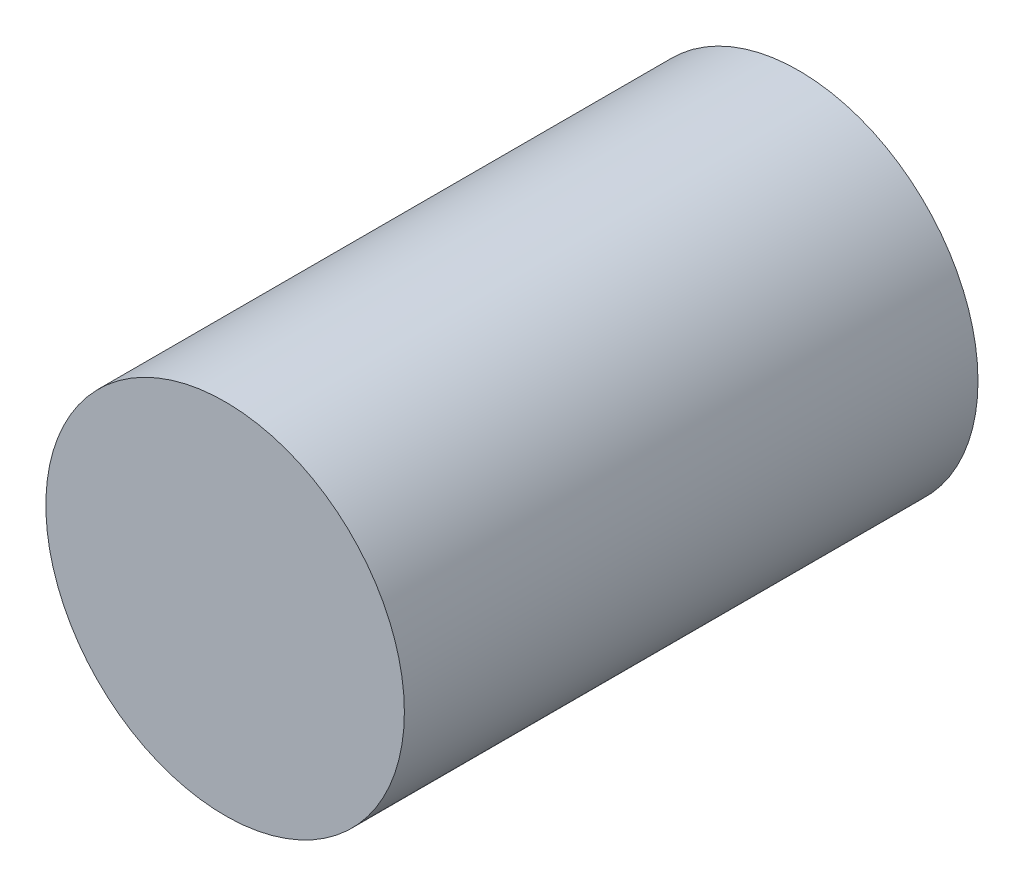
SolidWorks part; units mm, degrees
ref_plane "前视基准面" through (0, 0, 0) normal (0, 0, 1) x (1, 0, 0)
ref_plane "上视基准面" through (0, 0, 0) normal (0, 1, 0) x (1, 0, 0)
ref_plane "右视基准面" through (0, 0, 0) normal (1, 0, 0) x (0, 0, -1)
other "Configuration Table"
sketch "草图1" plane through (0, 0, 0) normal (0, 0, 1) x (1, 0, 0)
  circle A0 centre (0, 0) radius 1.5
  dimension "D1" = 3
extrude "凸台-拉伸1" add sketch "草图1" along normal blind 4.8
